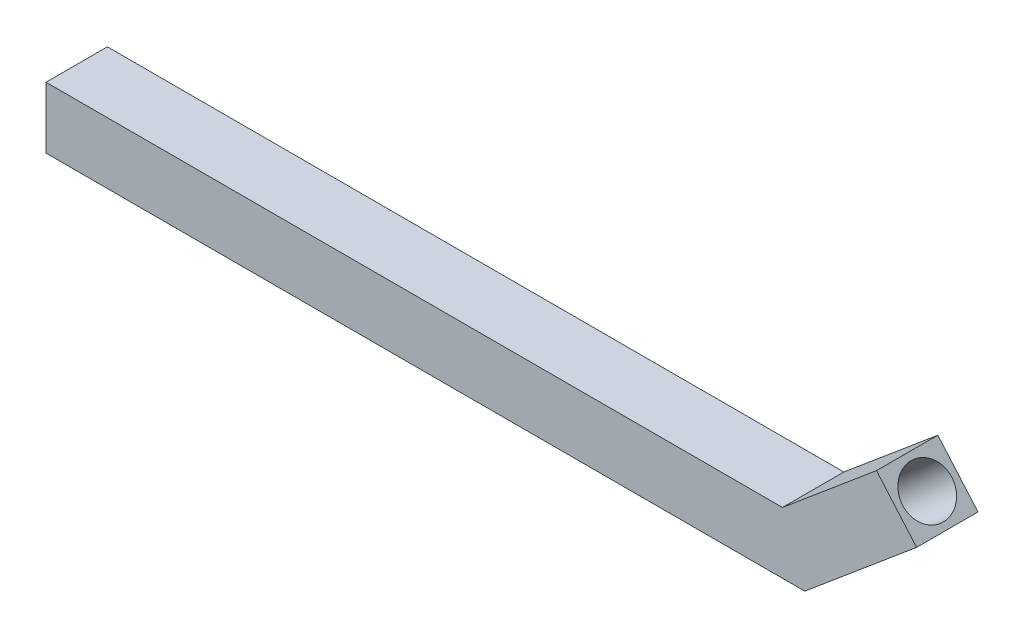
SolidWorks part; units mm, degrees
ref_plane "Front Plane" through (0, 0, 0) normal (0, 0, 1) x (1, 0, 0)
ref_plane "Top Plane" through (0, 0, 0) normal (0, 1, 0) x (1, 0, 0)
ref_plane "Right Plane" through (0, 0, 0) normal (1, 0, 0) x (0, 0, -1)
sketch "Sketch1" plane through (0, 0, 0) normal (0, 0, 1) x (1, 0, 0)
  line L0 (-5, 0) -> (0, 0)
  line L1 (0, 0) -> (3.8302, 3.2139)
  line L2 (-5, 0) -> (-5, -2.5)
  line L3 (-5, -2.5) -> (0.9095, -2.5)
  line L4 (0.9095, -2.5) -> (5.466, 1.3234)
  line L5 (5.466, 1.3234) -> (3.8302, 3.2139)
  dimension "D1" = 5
  dimension "D2" = 5
  dimension "D3" = 140
  dimension "D4" = 2.5
  dimension "D5" = 2.5
extrude "Boss-Extrude1" add sketch "Sketch1" along normal blind 2.5
sketch "Sketch2" plane through (3.7807, 3.2711, 0) normal (0.7562, 0.6543, 0) x (0, 0, -1)
  line L0 (-2.5, -1.3256) -> (0, -1.3256) construction
  line L1 (-2.5, -2.5756) -> (-2.5, -0.0756) construction
  line L2 (0, -2.5756) -> (0, -0.0756) construction
  line L3 (-1.25, -0.0756) -> (-1.25, -2.5756) construction
  line L4 (-2.5, -0.0756) -> (0, -0.0756) construction
  line L5 (-2.5, -2.5756) -> (0, -2.5756) construction
  circle A0 centre (-1.25, -1.3256) radius 1
  dimension "D1" = 2
extrude "Cut-Extrude1" cut sketch "Sketch2" against normal blind 5
sketch "Sketch3" plane through (-5, 0, 0) normal (-1, 0, 0) x (0, 0, 1)
  line L0 (1.25, 0) -> (1.25, -2.5) construction
  line L1 (2.5, 0) -> (0, 0) construction
  line L2 (2.5, -2.5) -> (0, -2.5) construction
  line L3 (0, -1.25) -> (2.5, -1.25) construction
  line L4 (0, 0) -> (0, -2.5) construction
  line L5 (2.5, 0) -> (2.5, -2.5) construction
  circle A0 centre (1.25, -1.25) radius 1
  dimension "D1" = 2
extrude "Cut-Extrude2" cut sketch "Sketch3" against normal blind 5
sketch "Sketch5" plane through (-5, 0, 0) normal (-1, 0, 0) x (0, 0, 1)
  line L0 (0, -1.25) -> (2.5, -1.25) construction
  line L1 (0, 0) -> (0, -2.5) construction
  line L2 (2.5, 0) -> (2.5, -2.5) construction
  line L3 (1.25, 0) -> (1.25, -2.5) construction
  line L4 (2.5, 0) -> (0, 0) construction
  line L5 (2.5, -2.5) -> (0, -2.5) construction
  circle A0 centre (1.25, -1.25) radius 1
extrude "Boss-Extrude2" add sketch "Sketch5" against normal blind 5
sketch "Sketch6" plane through (-5, 0, 0) normal (-1, 0, 0) x (0, 0, 1)
  line L0 (0, -1.25) -> (2.5, -1.25) construction
  line L1 (0, 0) -> (0, -2.5) construction
  line L2 (2.5, 0) -> (2.5, -2.5) construction
  line L3 (1.25, 0) -> (1.25, -2.5) construction
  line L4 (2.5, 0) -> (0, 0) construction
  line L5 (2.5, -2.5) -> (0, -2.5) construction
  line L7 (0, 0) -> (2.5, 0)
  line L8 (0, 0) -> (0, -2.5)
  line L9 (0, -2.5) -> (2.5, -2.5)
  line L10 (2.5, 0) -> (2.5, -2.5)
  line L11 (0, 0) -> (2.5, -2.5) construction
  line L12 (0, -2.5) -> (2.5, 0) construction
  point P12 (1.25, -1.25)
extrude "Boss-Extrude3" add sketch "Sketch6" along normal blind 25
sketch "Sketch7" plane through (-30, 0, 0) normal (-1, 0, 0) x (0, 0, 1)
  line L0 (0, -1.25) -> (2.5, -1.25) construction
  line L1 (0, 0) -> (0, -2.5) construction
  line L2 (2.5, -2.5) -> (2.5, 0) construction
  line L3 (1.25, 0) -> (1.25, -2.5) construction
  line L4 (2.5, 0) -> (0, 0) construction
  line L5 (0, -2.5) -> (2.5, -2.5) construction
  circle A0 centre (1.25, -1.25) radius 1
  dimension "D1" = 2
extrude "Cut-Extrude3" cut sketch "Sketch7" against normal blind 5
